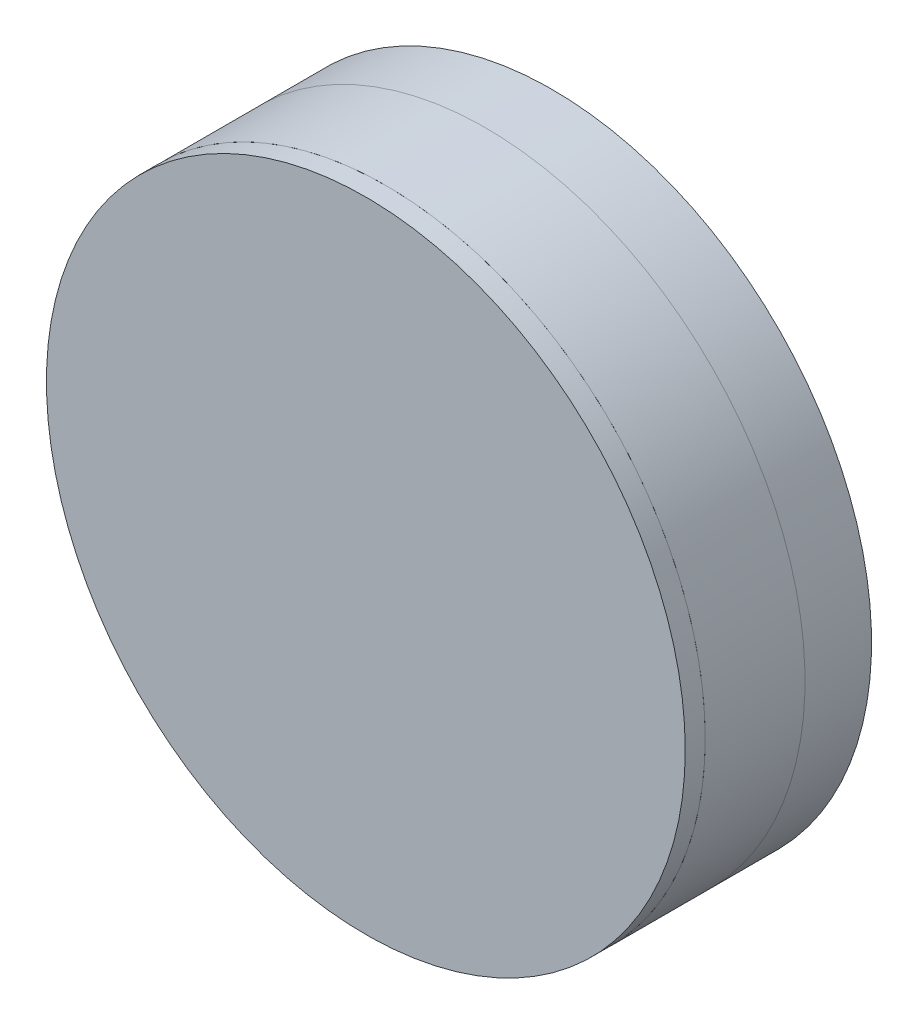
SolidWorks part; units mm, degrees
ref_plane "Front Plane" through (0, 0, 0) normal (0, 0, 1) x (1, 0, 0)
ref_plane "Top Plane" through (0, 0, 0) normal (0, 1, 0) x (1, 0, 0)
ref_plane "Right Plane" through (0, 0, 0) normal (1, 0, 0) x (0, 0, -1)
sketch "Sketch1" plane through (0, 0, 0) normal (0, 0, 1) x (1, 0, 0)
  circle A0 centre (0, 0) radius 48
extrude "Boss-Extrude1" add sketch "Sketch1" along normal blind 3
sketch "Sketch2" plane through (0, 0, 0) normal (0, 0, -1) x (-1, 0, 0)
  circle A1 centre (0, 0) radius 48
  circle A2 centre (0, 0) radius 48
  dimension "D1" = 0
extrude "Boss-Extrude3" add sketch "Sketch2" along normal blind 15 separate body
sketch "Sketch4" plane through (0, 0, -15) normal (0, 0, -1) x (-1, 0, 0)
  circle A1 centre (0, 0) radius 48
  circle A2 centre (0, 0) radius 48
  dimension "D1" = 0
extrude "Boss-Extrude4" add sketch "Sketch4" along normal blind 10 separate body
